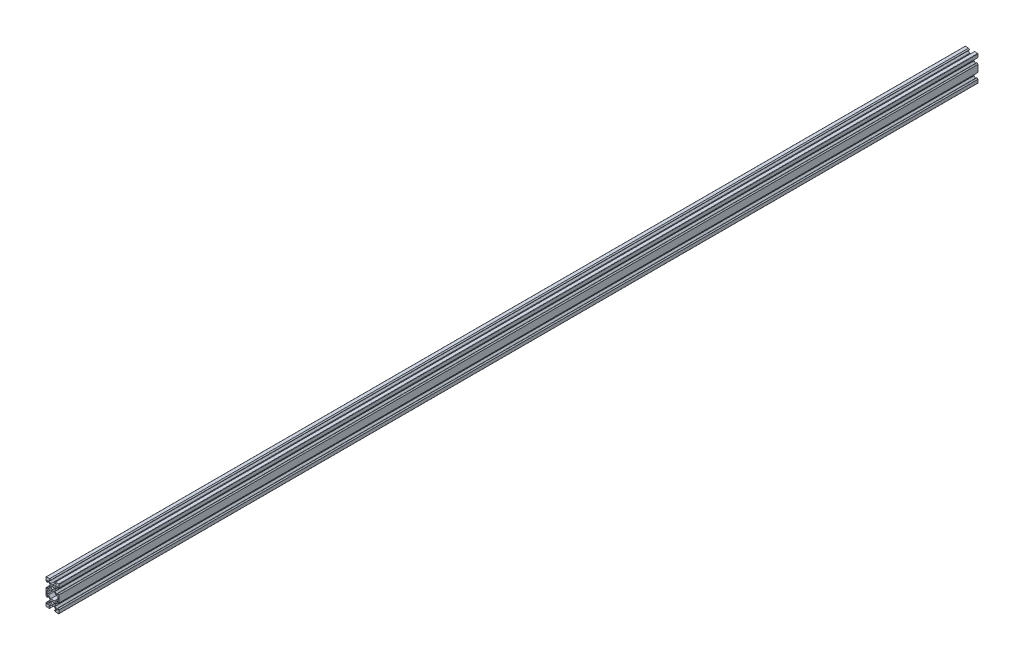
SolidWorks part; units mm, degrees
material "6061-T6 (SS)"
ref_plane "Front Plane" through (0, 0, 0) normal (0, 0, 1) x (1, 0, 0)
ref_plane "Top Plane" through (0, 0, 0) normal (0, 1, 0) x (1, 0, 0)
ref_plane "Right Plane" through (0, 0, 0) normal (1, 0, 0) x (0, 0, -1)
sketch "Sketch1" plane through (0, 0, 0) normal (0, 0, 1) x (1, 0, 0)
  line L0 (0, 0) -> (10, 0) construction
  line L1 (9.5, -20) -> (-9.5, -20)
  line L2 (10, -19.5) -> (10, 19.5)
  line L3 (9.5, 20) -> (-9.5, 20)
  line L4 (-10, -19.5) -> (-10, 19.5)
  line L5 (10, -20) -> (-10, 20) construction
  line L6 (10, 20) -> (-10, -20) construction
  circle A0 centre (0, 10) radius 2.1
  circle A1 centre (0, -10) radius 2.1
  arc A2 (-9.5, -20) -> (-10, -19.5) centre (-9.5, -19.5) cw
  arc A3 (9.5, -20) -> (10, -19.5) centre (9.5, -19.5) ccw
  arc A4 (10, 19.5) -> (9.5, 20) centre (9.5, 19.5) ccw
  arc A5 (-9.5, 20) -> (-10, 19.5) centre (-9.5, 19.5) ccw
  point P0 (0, 0)
  line B0 (0, 10) -> (0, 20) construction
  line B1 (0, 13.69) -> (-0.21, 13.9)
  line B2 (-0.21, 13.9) -> (-2.8393, 13.9)
  line B3 (-2.8393, 13.9) -> (-5.5, 16.5607)
  line B4 (-5.5, 16.5607) -> (-5.5, 18.2)
  line B5 (-5.5, 18.2) -> (-3.125, 18.2)
  line B6 (-3.125, 18.2) -> (-3.125, 18.545)
  line B7 (-3.125, 18.545) -> (-4.58, 20)
  line B8 (-4.58, 20) -> (4.58, 20)
  line B9 (0, 10) -> (-5.9132, 15.9132) construction
  line B10 (3.125, 18.545) -> (4.58, 20)
  line B11 (3.125, 18.2) -> (3.125, 18.545)
  line B12 (5.5, 18.2) -> (3.125, 18.2)
  line B13 (5.5, 16.5607) -> (5.5, 18.2)
  line B14 (2.8393, 13.9) -> (5.5, 16.5607)
  line B15 (0.21, 13.9) -> (2.8393, 13.9)
  line B16 (0, 13.69) -> (0.21, 13.9)
  line B17 (0, 10) -> (-10, 10) construction
  line B18 (-3.69, 10) -> (-3.9, 9.79)
  line B19 (-3.9, 9.79) -> (-3.9, 7.1607)
  line B20 (-3.9, 7.1607) -> (-6.5607, 4.5)
  line B21 (-6.5607, 4.5) -> (-8.2, 4.5)
  line B22 (-8.2, 4.5) -> (-8.2, 6.875)
  line B23 (-8.2, 6.875) -> (-8.545, 6.875)
  line B24 (-8.545, 6.875) -> (-10, 5.42)
  line B25 (-10, 5.42) -> (-10, 14.58)
  line B26 (0, 10) -> (-5.9132, 4.0868) construction
  line B27 (-8.545, 13.125) -> (-10, 14.58)
  line B28 (-8.2, 13.125) -> (-8.545, 13.125)
  line B29 (-8.2, 15.5) -> (-8.2, 13.125)
  line B30 (-6.5607, 15.5) -> (-8.2, 15.5)
  line B31 (-3.9, 12.8393) -> (-6.5607, 15.5)
  line B32 (-3.9, 10.21) -> (-3.9, 12.8393)
  line B33 (-3.69, 10) -> (-3.9, 10.21)
  line B34 (0, -10) -> (-10, -10) construction
  line B35 (-3.69, -10) -> (-3.9, -10.21)
  line B36 (-3.9, -10.21) -> (-3.9, -12.8393)
  line B37 (-3.9, -12.8393) -> (-6.5607, -15.5)
  line B38 (-6.5607, -15.5) -> (-8.2, -15.5)
  line B39 (-8.2, -15.5) -> (-8.2, -13.125)
  line B40 (-8.2, -13.125) -> (-8.545, -13.125)
  line B41 (-8.545, -13.125) -> (-10, -14.58)
  line B42 (-10, -14.58) -> (-10, -5.42)
  line B43 (0, -10) -> (-5.9132, -15.9132) construction
  line B44 (-8.545, -6.875) -> (-10, -5.42)
  line B45 (-8.2, -6.875) -> (-8.545, -6.875)
  line B46 (-8.2, -4.5) -> (-8.2, -6.875)
  line B47 (-6.5607, -4.5) -> (-8.2, -4.5)
  line B48 (-3.9, -7.1607) -> (-6.5607, -4.5)
  line B49 (-3.9, -9.79) -> (-3.9, -7.1607)
  line B50 (-3.69, -10) -> (-3.9, -9.79)
  line B51 (0, -10) -> (0, -20) construction
  line B52 (0, -13.69) -> (0.21, -13.9)
  line B53 (0.21, -13.9) -> (2.8393, -13.9)
  line B54 (2.8393, -13.9) -> (5.5, -16.5607)
  line B55 (5.5, -16.5607) -> (5.5, -18.2)
  line B56 (5.5, -18.2) -> (3.125, -18.2)
  line B57 (3.125, -18.2) -> (3.125, -18.545)
  line B58 (3.125, -18.545) -> (4.58, -20)
  line B59 (4.58, -20) -> (-4.58, -20)
  line B60 (0, -10) -> (5.9132, -15.9132) construction
  line B61 (-3.125, -18.545) -> (-4.58, -20)
  line B62 (-3.125, -18.2) -> (-3.125, -18.545)
  line B63 (-5.5, -18.2) -> (-3.125, -18.2)
  line B64 (-5.5, -16.5607) -> (-5.5, -18.2)
  line B65 (-2.8393, -13.9) -> (-5.5, -16.5607)
  line B66 (-0.21, -13.9) -> (-2.8393, -13.9)
  line B67 (0, -13.69) -> (-0.21, -13.9)
  line B68 (0, -10) -> (10, -10) construction
  line B69 (3.69, -10) -> (3.9, -9.79)
  line B70 (3.9, -9.79) -> (3.9, -7.1607)
  line B71 (3.9, -7.1607) -> (6.5607, -4.5)
  line B72 (6.5607, -4.5) -> (8.2, -4.5)
  line B73 (8.2, -4.5) -> (8.2, -6.875)
  line B74 (8.2, -6.875) -> (8.545, -6.875)
  line B75 (8.545, -6.875) -> (10, -5.42)
  line B76 (10, -5.42) -> (10, -14.58)
  line B77 (0, -10) -> (5.9132, -4.0868) construction
  line B78 (8.545, -13.125) -> (10, -14.58)
  line B79 (8.2, -13.125) -> (8.545, -13.125)
  line B80 (8.2, -15.5) -> (8.2, -13.125)
  line B81 (6.5607, -15.5) -> (8.2, -15.5)
  line B82 (3.9, -12.8393) -> (6.5607, -15.5)
  line B83 (3.9, -10.21) -> (3.9, -12.8393)
  line B84 (3.69, -10) -> (3.9, -10.21)
  line B85 (0, 10) -> (10, 10) construction
  line B86 (3.69, 10) -> (3.9, 10.21)
  line B87 (3.9, 10.21) -> (3.9, 12.8393)
  line B88 (3.9, 12.8393) -> (6.5607, 15.5)
  line B89 (6.5607, 15.5) -> (8.2, 15.5)
  line B90 (8.2, 15.5) -> (8.2, 13.125)
  line B91 (8.2, 13.125) -> (8.545, 13.125)
  line B92 (8.545, 13.125) -> (10, 14.58)
  line B93 (10, 14.58) -> (10, 5.42)
  line B94 (0, 10) -> (5.9132, 15.9132) construction
  line B95 (8.545, 6.875) -> (10, 5.42)
  line B96 (8.2, 6.875) -> (8.545, 6.875)
  line B97 (8.2, 4.5) -> (8.2, 6.875)
  line B98 (6.5607, 4.5) -> (8.2, 4.5)
  line B99 (3.9, 7.1607) -> (6.5607, 4.5)
  line B100 (3.9, 9.79) -> (3.9, 7.1607)
  line B101 (3.69, 10) -> (3.9, 9.79)
  line B102 (-8.2, -2.7) -> (-8.2, 2.7)
  line B103 (-8.2, 2.7) -> (-6.2393, 2.7)
  line B104 (-6.2393, 2.7) -> (-2.8393, 6.1)
  line B105 (-2.8393, 6.1) -> (2.8393, 6.1)
  line B106 (0, 6.1) -> (0, 0) construction
  line B107 (0, 0) -> (-8.2, 0) construction
  line B108 (6.2393, 2.7) -> (2.8393, 6.1)
  line B109 (8.2, 2.7) -> (6.2393, 2.7)
  line B110 (8.2, -2.7) -> (8.2, 2.7)
  line B111 (8.2, -2.7) -> (6.2393, -2.7)
  line B112 (6.2393, -2.7) -> (2.8393, -6.1)
  line B113 (-2.8393, -6.1) -> (2.8393, -6.1)
  line B114 (-6.2393, -2.7) -> (-2.8393, -6.1)
  line B115 (-8.2, -2.7) -> (-6.2393, -2.7)
  line B116 (0, 6.1) -> (0, 10) construction
  line B117 (0, 10) -> (-5.0927, 4.9073) construction
  dimension "D4" = 4.2
  dimension "D5" = 0.5
  dimension "D1" = 20
  dimension "D2" = 40
  dimension "D3" = 20
sketch_block_instance "V Slot 1-4"
sketch_block "V Slot 1" parameters "D1"=10, "D2"=11, "D3"=4.3, "D4"=1.8, "D5"=0.21, "D6"=45, "D7"=9.16, "D8"=1.5, "D9"=6.25
sketch_block_instance "V Slot 1-5"
sketch_block_instance "V Slot 1-6"
sketch_block_instance "V Slot 1-7"
sketch_block_instance "V Slot 1-8"
sketch_block_instance "V Slot 1-9"
sketch_block_instance "Center Cutout 1-1"
sketch_block "Center Cutout 1" parameters "D1"=5.4, "D2"=12.2, "D3"=8.2, "D4"=45, "D5"=10, "D6"=1.5
extrude "Boss-Extrude1" add sketch "Sketch1" along normal blind 1422.4 contours B101 B86 B87 B88 B89 B90 B91 B92 L2 A4 L3 B10 B11 B12 B13 B14 B15 B16 B1 B2 B3 B4 B5 B6 B7 A5 L4 B27 B28 B29 B30 B31 B32 B33 B18 B19 B20 B21 B22 B23 B24 B44 B45 B46 B47 B48 B49 B50 B35
